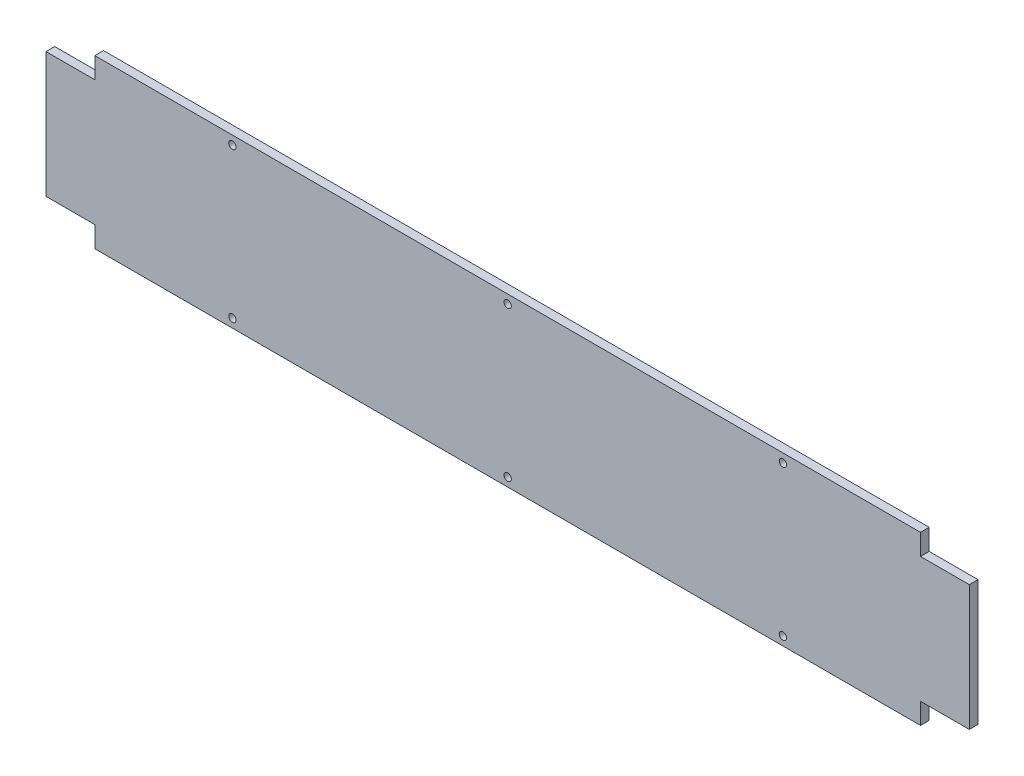
SolidWorks part; units mm, degrees
ref_plane "Front Plane" through (0, 0, 0) normal (0, 0, 1) x (1, 0, 0)
ref_plane "Top Plane" through (0, 0, 0) normal (0, 1, 0) x (1, 0, 0)
ref_plane "Right Plane" through (0, 0, 0) normal (1, 0, 0) x (0, 0, -1)
sketch "Sketch1" plane through (0, 0, 0) normal (0, 0, 1) x (1, 0, 0)
  line L1 (0, 0) -> (474, 0)
  line L2 (0, 0) -> (0, 96)
  line L3 (0, 96) -> (474, 96)
  line L4 (474, 0) -> (474, 96)
  dimension "D1" = 96
  dimension "D2" = 474
extrude "Boss-Extrude1" add sketch "Sketch1" along normal blind 5
sketch "Sketch2" plane through (0, 0, 5) normal (0, 0, 1) x (1, 0, 0)
  line L0 (474, 96) -> (0, 96) construction
  line L1 (0, 96) -> (0, 0) construction
  line L2 (168.4658, 48) -> (329.5293, 48) construction
  circle A0 centre (79, 91) radius 2.1
  circle A1 centre (237, 91) radius 2.1
  circle A2 centre (395, 91) radius 2.1
  circle A3 centre (395, 5) radius 2.1
  circle A4 centre (237, 5) radius 2.1
  circle A5 centre (79, 5) radius 2.1
  dimension "D1" = 4.2
  dimension "D2" = 4.2
  dimension "D3" = 4.2
  dimension "D4" = 5
  dimension "D5" = 79
  dimension "D6" = 158
  dimension "D7" = 158
  dimension "D8" = 48
extrude "Cut-Extrude1" cut sketch "Sketch2" against normal blind 5
sketch "Sketch3" plane through (0, 0, 5) normal (0, 0, 1) x (1, 0, 0)
  line L0 (474, 0) -> (474, 96) construction
  line L1 (474, 84) -> (502, 84)
  line L2 (474, 84) -> (474, 12)
  line L3 (474, 12) -> (502, 12)
  line L4 (502, 84) -> (502, 12)
  line L5 (0, 96) -> (0, 0) construction
  line L6 (0, 84) -> (-28, 84)
  line L7 (0, 84) -> (0, 12)
  line L8 (0, 12) -> (-28, 12)
  line L9 (-28, 84) -> (-28, 12)
  line L10 (0, 0) -> (474, 0) construction
  line L11 (474, 96) -> (0, 96) construction
  dimension "D1" = 28
  dimension "D2" = 12
  dimension "D3" = 12
  dimension "D4" = 12
  dimension "D5" = 12
  dimension "D6" = 28
extrude "Boss-Extrude2" add sketch "Sketch3" against normal blind 5
